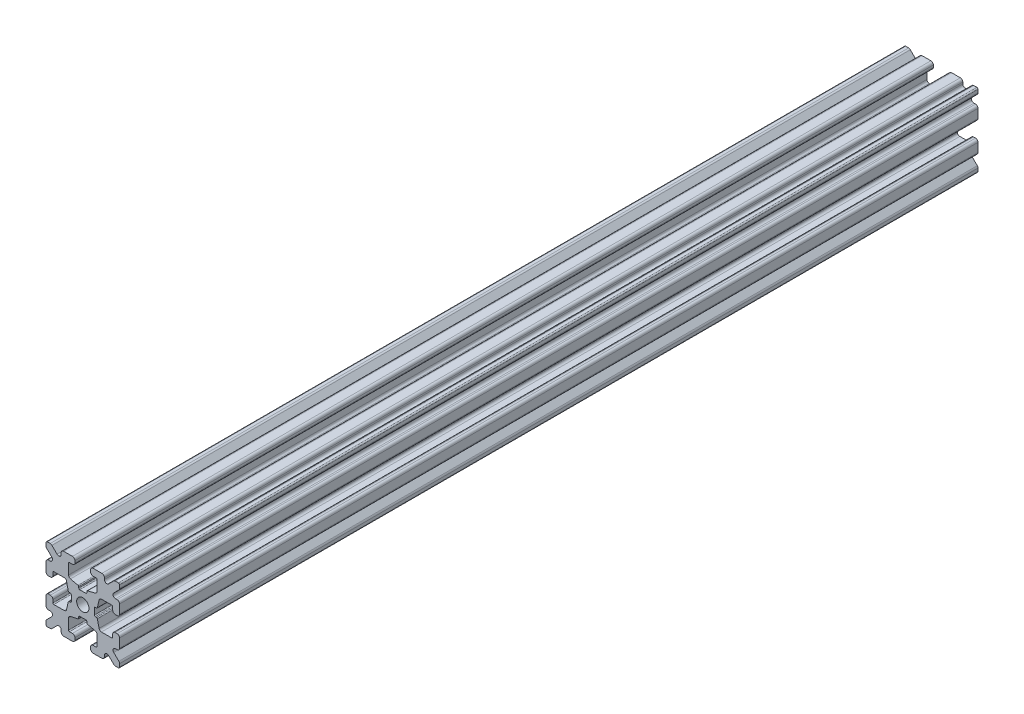
SolidWorks part; units mm, degrees
ref_plane "Front Plane" through (0, 0, 0) normal (0, 0, 1) x (1, 0, 0)
ref_plane "Top Plane" through (0, 0, 0) normal (0, 1, 0) x (1, 0, 0)
ref_plane "Right Plane" through (0, 0, 0) normal (1, 0, 0) x (0, 0, -1)
sketch "Sketch1" plane through (0, 0, 0) normal (0, 0, 1) x (1, 0, 0)
  line L1 (-7.5, -7.5) -> (7.5, -7.5)
  line L2 (-7.5, -7.5) -> (-7.5, 7.5)
  line L3 (-7.5, 7.5) -> (7.5, 7.5)
  line L4 (7.5, -7.5) -> (7.5, 7.5)
  line L5 (-7.5, -7.5) -> (7.5, 7.5) construction
  line L6 (-7.5, 7.5) -> (7.5, -7.5) construction
  circle A0 centre (0, 0) radius 1.25
  point P0 (0, 0)
  dimension "D2" = 2.5
  dimension "D1" = 15
extrude "Boss-Extrude1" add sketch "Sketch1" along normal mid plane 175
fillet "Fillet1" radius 0.25 4 edges at (7.5, -7.5, 0) (-7.5, -7.5, 0) (7.5, 7.5, 0) (-7.5, 7.5, 0)
sketch "Sketch2" plane through (0, 0, 87.5) normal (0, 0, 1) x (1, 0, 0)
  line L0 (-7.5, 7.25) -> (-7.5, -7.25) construction
  line L1 (-7.5, 1.6) -> (-6.1, 1.6)
  line L2 (-7.5, 1.6) -> (-7.5, -1.6)
  line L3 (-7.5, -1.6) -> (-6.1, -1.6)
  line L4 (-6.1, 1.6) -> (-6.1, 2.9)
  line L5 (0, 0) -> (-12.1036, 0) construction
  line L6 (-6.1, -2.9) -> (-3.4, -2.9)
  line L7 (0, 0) -> (-7.25, 7.25) construction
  line L8 (-6.1, 2.9) -> (-3.4, 2.9)
  line L9 (-3.4, -2.9) -> (-3.4, 2.9)
  line L10 (55, 0) -> (-55, 0) construction
  line L11 (-6.1, -2.9) -> (-6.1, -1.6)
  line L12 (2.9, 6.1) -> (1.6, 6.1)
  line L13 (2.9, 3.4) -> (-2.9, 3.4)
  line L14 (-2.9, 6.1) -> (-2.9, 3.4)
  line L15 (2.9, 6.1) -> (2.9, 3.4)
  line L16 (-1.6, 6.1) -> (-2.9, 6.1)
  line L17 (1.6, 7.5) -> (1.6, 6.1)
  line L18 (-1.6, 7.5) -> (1.6, 7.5)
  line L19 (-1.6, 7.5) -> (-1.6, 6.1)
  line L20 (-1.6, -7.5) -> (-1.6, -6.1)
  line L21 (-1.6, -7.5) -> (1.6, -7.5)
  line L22 (1.6, -7.5) -> (1.6, -6.1)
  line L23 (-1.6, -6.1) -> (-2.9, -6.1)
  line L24 (2.9, -6.1) -> (2.9, -3.4)
  line L25 (-2.9, -6.1) -> (-2.9, -3.4)
  line L26 (2.9, -3.4) -> (-2.9, -3.4)
  line L27 (2.9, -6.1) -> (1.6, -6.1)
  line L28 (6.1, -2.9) -> (6.1, -1.6)
  line L29 (3.4, -2.9) -> (3.4, 2.9)
  line L30 (6.1, 2.9) -> (3.4, 2.9)
  line L31 (6.1, -2.9) -> (3.4, -2.9)
  line L32 (6.1, 1.6) -> (6.1, 2.9)
  line L33 (7.5, -1.6) -> (6.1, -1.6)
  line L34 (7.5, 1.6) -> (7.5, -1.6)
  line L35 (7.5, 1.6) -> (6.1, 1.6)
  dimension "D1" = 3.2
  dimension "D2" = 5.8
  dimension "D3" = 1.4
  dimension "D4" = 2.7
extrude "Cut-Extrude1" cut sketch "Sketch2" against normal through all
sketch "Sketch4" plane through (0, 0, 87.5) normal (0, 0, 1) x (1, 0, 0)
  line L0 (-3.4, 2.9) -> (-2.75, 0)
  line L1 (55, 0) -> (-55, 0) construction
  line L2 (-2.75, 0) -> (-3.4, -2.9)
  line L3 (-3.4, -2.9) -> (-3.4, 2.9) construction
  line L4 (-3.4, 2.9) -> (-3.4, -2.9)
  line L5 (-2.9, 3.4) -> (0, 2.75)
  line L6 (0, 2.75) -> (2.9, 3.4)
  line L7 (2.9, 3.4) -> (-2.9, 3.4)
  line L8 (3.4, 2.9) -> (2.75, 0)
  line L9 (2.75, 0) -> (3.4, -2.9)
  line L10 (3.4, -2.9) -> (3.4, 2.9)
  line L11 (-2.9, -3.4) -> (0, -2.75)
  line L12 (0, -2.75) -> (2.9, -3.4)
  line L13 (2.9, -3.4) -> (-2.9, -3.4)
  circle A2 centre (0, 0) radius 2.75
  circle A3 centre (0, 0) radius 2.75 construction
  dimension "D1" = 1.5
extrude "Cut-Extrude3" cut sketch "Sketch4" against normal through all
fillet "Fillet3" radius 0.5 16 edges at (-6.1, -1.6, 0) (-7.5, -1.6, 0) (-6.1, 1.6, 0) (-7.5, 1.6, 0) (-1.6, -7.5, 0) (-1.6, -6.1, 0) (1.6, -7.5, 0) (1.6, -6.1, 0) (6.1, -1.6, 0) (7.5, -1.6, 0) (7.5, 1.6, 0) (6.1, 1.6, 0) (1.6, 7.5, 0) (1.6, 6.1, 0) (-1.6, 7.5, 0) (-1.6, 6.1, 0)
fillet "Fillet4" radius 0.5 8 edges at (-3.4, 2.9, 0) (-3.4, -2.9, 0) (2.9, -3.4, 0) (-2.9, -3.4, 0) (3.4, -2.9, 0) (3.4, 2.9, 0) (-2.9, 3.4, 0) (2.9, 3.4, 0)
fillet "Fillet5" radius 3 4 edges at (0, -2.75, 0) (2.75, 0, 0) (-2.75, 0, 0) (0, 2.75, 0)
fillet "Fillet6" radius 0.2 8 edges at (-2.9, -6.1, 0) (2.9, -6.1, 0) (6.1, -2.9, 0) (6.1, 2.9, 0) (2.9, 6.1, 0) (-2.9, 6.1, 0) (-6.1, -2.9, 0) (-6.1, 2.9, 0)
sketch "Sketch5" plane through (0, 0, 87.5) normal (0, 0, 1) x (1, 0, 0)
  line L0 (0, 0) -> (-7.25, 7.25) construction
  line L1 (-7.5, 6.4393) -> (-5.4607, 4.4)
  line L2 (-6.4393, 7.5) -> (-4.4, 5.4607)
  line L3 (-7.5, 4.4) -> (-5.4607, 4.4)
  line L4 (-3.8003, 2.9) -> (-5.9, 2.9) construction
  line L5 (0, 0) -> (-12.1819, 0) construction
  line L6 (-4.4, 7.5) -> (-4.4, 5.4607)
  line L7 (-2.9, 5.9) -> (-2.9, 3.8003) construction
  line L8 (-7.5, 6.4393) -> (-7.5, 4.4)
  line L9 (-7.5, 7.25) -> (-7.5, 2.1) construction
  line L10 (2.1, -7.5) -> (7.25, -7.5) construction
  line L11 (7.5, -7.25) -> (7.5, -2.1) construction
  line L12 (7.25, 7.5) -> (2.1, 7.5) construction
  line L13 (-2.1, 7.5) -> (-7.25, 7.5) construction
  line L14 (-4.4, 7.5) -> (-6.4393, 7.5)
  line L16 (55, 0) -> (-55, 0) construction
  line L17 (0, 0) -> (0, 10.993) construction
  line L18 (0, -54.6431) -> (0, 54.6431) construction
  line L20 (4.4, 7.5) -> (6.4393, 7.5)
  line L22 (7.5, 6.4393) -> (7.5, 4.4)
  line L23 (4.4, 7.5) -> (4.4, 5.4607)
  line L24 (7.5, 4.4) -> (5.4607, 4.4)
  line L25 (6.4393, 7.5) -> (4.4, 5.4607)
  line L26 (7.5, 6.4393) -> (5.4607, 4.4)
  line L27 (7.5, -6.4393) -> (5.4607, -4.4)
  line L28 (6.4393, -7.5) -> (4.4, -5.4607)
  line L29 (7.5, -4.4) -> (5.4607, -4.4)
  line L30 (4.4, -7.5) -> (4.4, -5.4607)
  line L31 (7.5, -6.4393) -> (7.5, -4.4)
  line L33 (4.4, -7.5) -> (6.4393, -7.5)
  line L36 (-4.4, -7.5) -> (-6.4393, -7.5)
  line L38 (-7.5, -6.4393) -> (-7.5, -4.4)
  line L39 (-4.4, -7.5) -> (-4.4, -5.4607)
  line L40 (-7.5, -4.4) -> (-5.4607, -4.4)
  line L41 (-6.4393, -7.5) -> (-4.4, -5.4607)
  line L42 (-7.5, -6.4393) -> (-5.4607, -4.4)
  dimension "D1" = 1.5
  dimension "D2" = 1.5
  dimension "D3" = 1.5
extrude "Cut-Extrude4" cut sketch "Sketch5" against normal through all
fillet "Fillet8" radius 0.5 24 edges at (-5.4607, 4.4, 0) (-7.5, 4.4, 0) (-5.4607, -4.4, 0) (-7.5, -4.4, 0) (-4.4, -7.5, 0) (-4.4, -5.4607, 0) (4.4, -7.5, 0) (4.4, -5.4607, 0) (5.4607, -4.4, 0) (7.5, -4.4, 0) (7.5, 4.4, 0) (5.4607, 4.4, 0) (4.4, 5.4607, 0) (4.4, 7.5, 0) (-4.4, 5.4607, 0) (-4.4, 7.5, 0) (-6.4393, 7.5, 0) (-7.5, 6.4393, 0) (6.4393, 7.5, 0) (7.5, 6.4393, 0) (6.4393, -7.5, 0) (7.5, -6.4393, 0) (-6.4393, -7.5, 0) (-7.5, -6.4393, 0)
sketch "Sketch6" plane through (0, 0, 87.5) normal (0, 0, 1) x (1, 0, 0)
  line L0 (0, 0) -> (0, 11.013) construction
  line L1 (0.6561, 2.8971) -> (2.1235, 2.8971) construction
  line L2 (0, -54.6431) -> (0, 54.6431) construction
  line L3 (0, 0) -> (7.25, 7.25) construction
  line L4 (7.5, 0.8255) -> (7.5, -0.8255)
  line L5 (2.3471, 0.8255) -> (7.5, 0.8255)
  line L6 (0, 0) -> (12.4016, 0) construction
  line L7 (0.8255, -7.5) -> (-0.8255, -7.5)
  line L8 (2.3471, -0.8255) -> (2.3471, 0.8255)
  line L9 (0.8255, -2.3471) -> (0.8255, -7.5)
  line L10 (7.5, -0.8255) -> (2.3471, -0.8255)
  line L11 (-7.5, -0.8255) -> (-2.3471, -0.8255)
  line L12 (-2.3471, -0.8255) -> (-2.3471, 0.8255)
  line L13 (-0.8255, -2.3471) -> (0.8255, -2.3471)
  line L14 (-0.8255, 7.5) -> (-0.8255, 2.3471)
  line L15 (-0.8255, 2.3471) -> (0.8255, 2.3471)
  line L16 (-0.8255, -7.5) -> (-0.8255, -2.3471)
  line L17 (0.8255, 2.3471) -> (0.8255, 7.5)
  line L18 (0.8255, 7.5) -> (-0.8255, 7.5)
  line L19 (3.9, 7.5) -> (2.1, 7.5) construction
  line L20 (-2.3471, 0.8255) -> (-7.5, 0.8255)
  line L21 (-7.5, 0.8255) -> (-7.5, -0.8255)
  point P5 (0, -2.5973)
  point P7 (0, 2.5973)
  dimension "D3" = 0.55
  dimension "D1" = 1.651
extrude "Cut-Extrude5" cut sketch "Sketch6" against normal through all
fillet "Fillet10" radius 0.2 16 edges at (-2.935, 0.8255, 0) (-2.935, -0.8255, 0) (2.935, -0.8255, 0) (2.935, 0.8255, 0) (0.8255, 2.935, 0) (-0.8255, 2.935, 0) (-2.3471, 0.8255, 0) (-2.3471, -0.8255, 0) (0.8255, 2.3471, 0) (-0.8255, 2.3471, 0) (2.3471, 0.8255, 0) (2.3471, -0.8255, 0) (0.8255, -2.935, 0) (0.8255, -2.3471, 0) (-0.8255, -2.3471, 0) (-0.8255, -2.935, 0)
